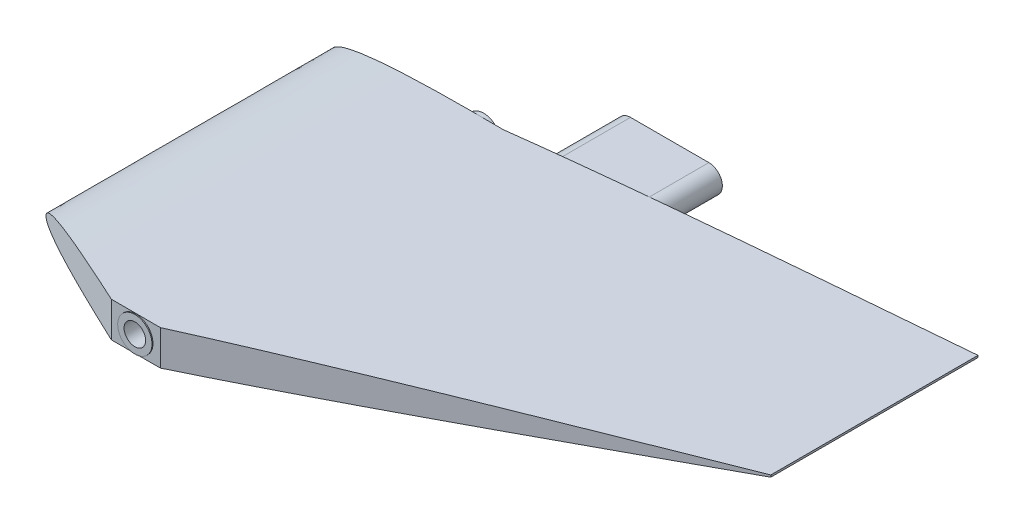
SolidWorks part; units mm, degrees
ref_plane "Front Plane" through (0, 0, 0) normal (0, 0, 1) x (1, 0, 0)
ref_plane "Top Plane" through (0, 0, 0) normal (0, 1, 0) x (1, 0, 0)
ref_plane "Right Plane" through (0, 0, 0) normal (1, 0, 0) x (0, 0, -1)
sketch "Sketch1" plane through (0, 0, 0) normal (0, 0, 1) x (1, 0, 0)
  line L0 (-15, 0) -> (-15, -2.6956) construction
  line L1 (0, 0) -> (-24865.1116, 0) construction
  line L2 (-19.5151, 1.8079) -> (14.7756, 1.8079) construction
  line L3 (-15, 0) -> (44.9999, 0)
  line L4 (44.9999, 0) -> (44.9999, 0.1)
  spline S0 degree 3 poles (-15, 0) (-15, 3.231) (19.0771, 1.4031) (44.9999, 0.1) knots 0 0 0 0 1 1 1 1
  dimension "D1" = 1.8079
  dimension "D2" = 60
  dimension "D3" = 0.1
  dimension "D4" = 15
extrude "Boss-Extrude1" add sketch "Sketch1" along normal blind 50 contours S0 L4 L3
mirror "Mirror1" about plane through (-15, 0, 50) normal (0, 1, 0) of "Boss-Extrude1"
sketch "Sketch2" plane through (0, 0, 0) normal (0, 1, 0) x (1, 0, 0)
  line L0 (-27.642, -50) -> (50.6593, -50) construction
  line L1 (-15, -50) -> (44.9999, -50) construction
  line L2 (-26.5228, -38.798) -> (-2.5, -50)
  line L3 (-2.5, -50) -> (2.5, -50)
  line L4 (2.5, -50) -> (51.7922, -27.0147)
  line L5 (51.7922, -27.0147) -> (51.7922, -55.1159)
  line L6 (51.7922, -55.1159) -> (-26.5228, -55.1159)
  line L7 (-26.5228, -55.1159) -> (-26.5228, -38.798)
  line L8 (-15, -62.14) -> (-15, 22.2853) construction
  line L9 (-15, -50) -> (-15, 0) construction
  line L10 (-24.9323, -15) -> (52.3257, -15) construction
  line L11 (0, -50) -> (0, 20) construction
  line L12 (-2.5, -15) -> (2.5, -15)
  line L13 (-2.5, -15) -> (-23.6947, -15)
  line L14 (-23.6947, -15) -> (-23.6947, 7.0335)
  line L15 (-23.6947, 7.0335) -> (50.3549, 7.0335)
  line L16 (50.3549, 7.0335) -> (50.3549, -8.2744)
  line L17 (50.3549, -8.2744) -> (2.5, -15)
  point P14 (0, -50)
  point P23 (0, -15)
  dimension "D1" = 15
  dimension "D2" = 5
  dimension "D3" = 25
  dimension "D4" = 25
  dimension "D5" = 35
  dimension "D6" = 8
  dimension "D7" = 0
extrude "Cut-Extrude1" cut sketch "Sketch2" against normal through all both and the other way through all
sketch "Sketch3" plane through (0, 0, 50) normal (0, 0, 1) x (1, 0, 0)
  line L0 (0, -4.0569) -> (0, 6.5289) construction
  line L1 (-3.4021, 0) -> (0.829, 0) construction
  line L2 (-2.5, -1.7987) -> (-2.5, 1.7987) construction
  line L3 (2.5, -1.7911) -> (2.5, 1.7911) construction
  line L4 (-9.2245, -1.8079) -> (7.7387, -1.8079) construction
  line L5 (-11.2019, 1.8079) -> (8.6925, 1.8079) construction
  circle A0 centre (0, 0) radius 1.75
  spline S6 degree 3 poles (-2.5, 1.7987) (-0.938, 1.8135) (0.7355, 1.81) (2.5, 1.7911) knots 0.380927 0.380927 0.380927 0.380927 0.45968 0.45968 0.45968 0.45968 construction
  spline S7 degree 3 poles (-2.5, -1.7987) (-0.938, -1.8135) (0.7355, -1.81) (2.5, -1.7911) knots 0.380927 0.380927 0.380927 0.380927 0.45968 0.45968 0.45968 0.45968 construction
  dimension "D1" = 3.5
extrude "Boss-Extrude2" add sketch "Sketch3" along normal blind 0.1
sketch "Sketch5" plane through (0, 0, 15) normal (0, 0, -1) x (-1, 0, 0)
  circle A0 centre (0, 0) radius 1.75 construction
  circle A1 centre (0, 0) radius 1.75
extrude "Boss-Extrude3" add sketch "Sketch5" along normal blind 0.5
sketch "Sketch4" plane through (0, 0, 50.1) normal (0, 0, 1) x (1, 0, 0)
  circle A0 centre (0, 0) radius 1.1
  dimension "D1" = 2.2
extrude "Cut-Extrude2" cut sketch "Sketch4" against normal through all
ref_plane "Plane1" through (0, 0, 9) normal (0, 0, -1) x (-1, 0, 0)
sketch "Sketch6" plane through (0, 0, 9) normal (0, 0, -1) x (-1, 0, 0)
  line L0 (-7.5, 0) -> (-15.5, 0) construction
  line L1 (-7.5, -1.375) -> (-15.5, -1.375)
  line L2 (-7.5, 1.375) -> (-15.5, 1.375)
  arc A0 (-7.5, -1.375) -> (-7.5, 1.375) centre (-7.5, 0) ccw
  arc A1 (-15.5, 1.375) -> (-15.5, -1.375) centre (-15.5, 0) ccw
  point P0 (-9.2742, 0)
  point P4 (-11.5, 0)
  dimension "D1" = 2.75
  dimension "D2" = 8
  dimension "D3" = 7.5
extrude "Boss-Extrude4" add sketch "Sketch6" against normal up to next
sketch "Sketch7" plane through (0, 0, 9) normal (0, 0, -1) x (-1, 0, 0)
  line L0 (-16.429, -1.0137) -> (-2.0268, -14.2118)
  line L1 (2.3446, -10.1284) -> (-6.4254, 0.8578)
  line L3 (-7.5, 1.375) -> (-15.5, 1.375) construction
  line L4 (-15.5, 1.375) -> (-7.5, 1.375)
  arc A0 (-2.0268, -14.2118) -> (2.3446, -10.1284) centre (0, -12) ccw
  arc A3 (-15.5, 1.375) -> (-16.7795, 0.5035) centre (-15.5, 0) ccw construction
  arc A4 (-7.1907, 1.3398) -> (-7.5, 1.375) centre (-7.5, 0) ccw construction
  arc A5 (-16.429, -1.0137) -> (-15.5, 1.375) centre (-15.5, 0) cw
  arc A6 (-6.4254, 0.8578) -> (-7.5, 1.375) centre (-7.5, 0) ccw
  arc A7 (-7.5, -1.375) -> (-7.5, 1.375) centre (-7.5, 0) ccw construction
  arc A8 (-15.5, 1.375) -> (-15.5, -1.375) centre (-15.5, 0) ccw construction
  dimension "D1" = 3
  dimension "D2" = 12
extrude "Boss-Extrude5" add sketch "Sketch7" along normal blind 2
sketch "Sketch8" plane through (0, 0, 7) normal (0, 0, -1) x (-1, 0, 0)
  circle A0 centre (0, -12) radius 0.625
  arc A1 (-2.0268, -14.2118) -> (2.3446, -10.1284) centre (0, -12) ccw construction
  dimension "D1" = 1.25
extrude "Cut-Extrude3" cut sketch "Sketch8" against normal through all
